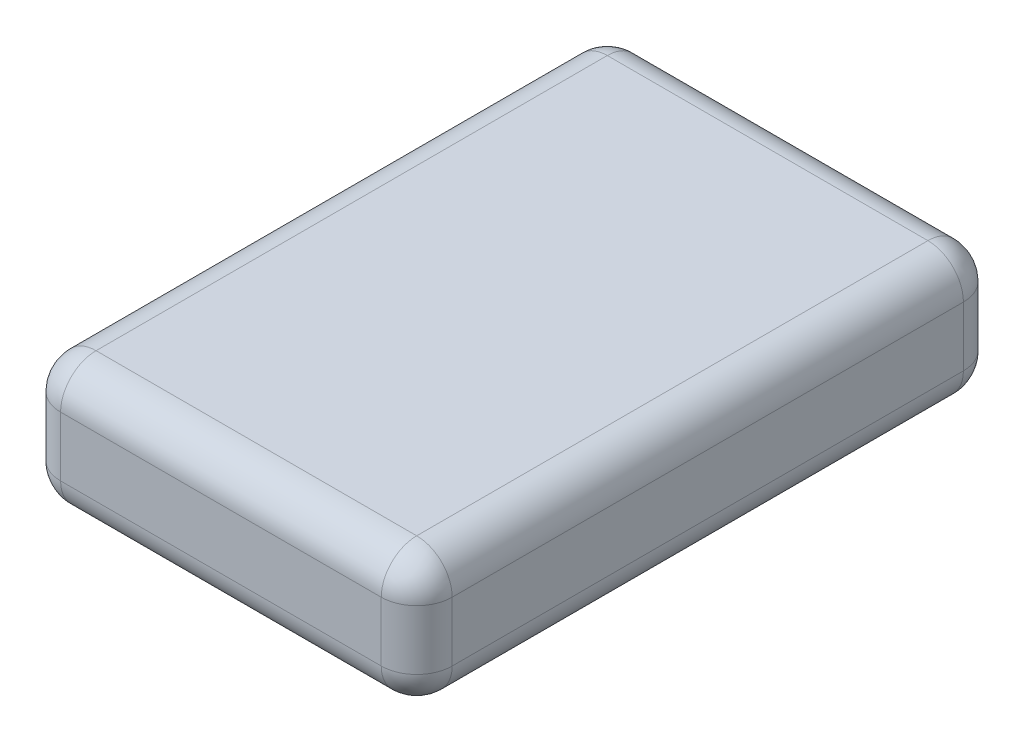
SolidWorks part; units mm, degrees
ref_plane "Front Plane" through (0, 0, 0) normal (0, 0, 1) x (1, 0, 0)
ref_plane "Top Plane" through (0, 0, 0) normal (0, 1, 0) x (1, 0, 0)
ref_plane "Right Plane" through (0, 0, 0) normal (1, 0, 0) x (0, 0, -1)
sketch "Sketch1" plane through (0, 0, 0) normal (0, 1, 0) x (1, 0, 0)
  line L1 (-8.28, -12.31) -> (8.28, -12.31)
  line L2 (-8.28, -12.31) -> (-8.28, 12.31)
  line L3 (-8.28, 12.31) -> (8.28, 12.31)
  line L4 (8.28, -12.31) -> (8.28, 12.31)
  line L5 (-8.28, -12.31) -> (8.28, 12.31) construction
  line L6 (-8.28, 12.31) -> (8.28, -12.31) construction
  point P0 (0, 0)
  dimension "D1" = 16.56
  dimension "D2" = 24.62
extrude "Boss-Extrude1" add sketch "Sketch1" along normal blind 5.52
fillet "Fillet1" radius 1.5 12 edges at (0, 0, -12.31) (8.28, 2.76, -12.31) (8.28, 2.76, 12.31) (-8.28, 2.76, 12.31) (-8.28, 5.52, 0) (-8.28, 2.76, -12.31) (0, 5.52, -12.31) (-8.28, 0, 0) (8.28, 0, 0) (8.28, 5.52, 0) (0, 0, 12.31) (0, 5.52, 12.31)
